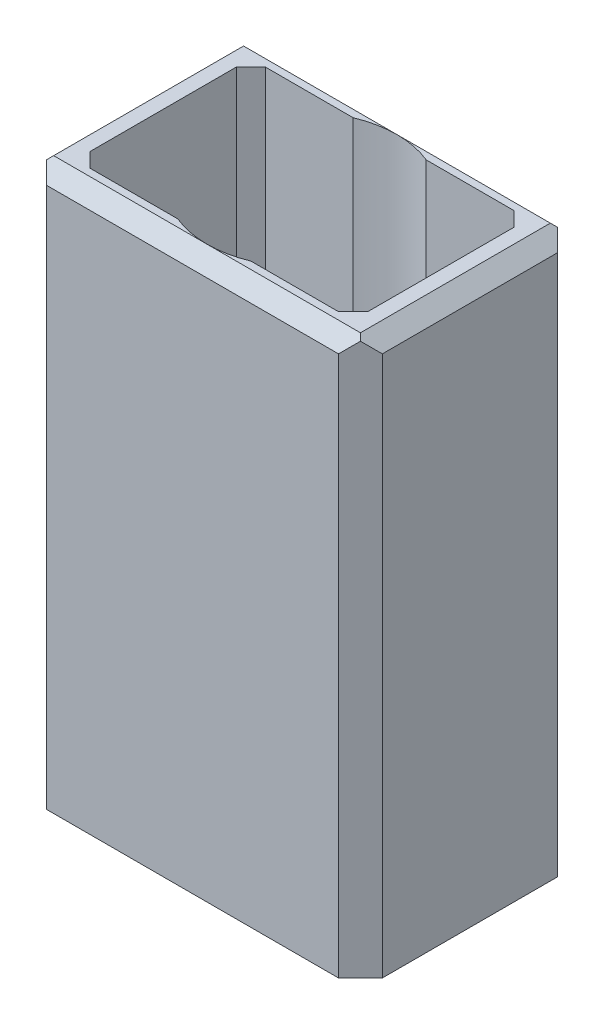
SolidWorks part; units mm, degrees
ref_plane "Front Plane" through (0, 0, 0) normal (0, 0, 1) x (1, 0, 0)
ref_plane "Top Plane" through (0, 0, 0) normal (0, 1, 0) x (1, 0, 0)
ref_plane "Right Plane" through (0, 0, 0) normal (1, 0, 0) x (0, 0, -1)
sketch "Sketch1" plane through (0, 0, 0) normal (0, 1, 0) x (1, 0, 0)
  line L1 (-9.5, -6) -> (9.5, -6)
  line L2 (-9.5, -6) -> (-9.5, 6)
  line L3 (-9.5, 6) -> (9.5, 6)
  line L4 (9.5, -6) -> (9.5, 6)
  line L5 (-9.5, -6) -> (9.5, 6) construction
  line L6 (-9.5, 6) -> (9.5, -6) construction
  line L7 (-11.5, -7.5) -> (11.5, -7.5)
  line L8 (-11.5, -7.5) -> (-11.5, 7.5)
  line L9 (-11.5, 7.5) -> (11.5, 7.5)
  line L10 (11.5, -7.5) -> (11.5, 7.5)
  line L11 (-11.5, -7.5) -> (11.5, 7.5) construction
  line L12 (-11.5, 7.5) -> (11.5, -7.5) construction
  point P0 (0, 0)
  point P6 (0, 0)
  dimension "D1" = 19
  dimension "D2" = 12
  dimension "D3" = 1.5
  dimension "D4" = 2
extrude "Boss-Extrude1" add sketch "Sketch1" along normal blind 35
chamfer "Chamfer1" distance 1 angle 45 4 edges at (-11.5, 35, 0) (0, 35, -7.5) (11.5, 35, 0) (0, 35, 7.5)
chamfer "Chamfer2" distance 1 angle 45 4 edges at (-9.5, 17.5, 6) (9.5, 17.5, 6) (-9.5, 17.5, -6) (9.5, 17.5, -6)
sketch "Sketch2" plane through (0, 0, 0) normal (0, -1, 0) x (1, 0, 0)
  line L1 (11.5, -7.5) -> (-11.5, -7.5)
  line L2 (11.5, -7.5) -> (11.5, 7.5)
  line L3 (11.5, 7.5) -> (-11.5, 7.5)
  line L4 (-11.5, -7.5) -> (-11.5, 7.5)
  line L5 (11.5, -7.5) -> (-11.5, 7.5) construction
  line L6 (11.5, 7.5) -> (-11.5, -7.5) construction
  point P0 (0, 0)
extrude "Boss-Extrude2" add sketch "Sketch2" along normal blind 3
chamfer "Chamfer4" distance 1.5 angle 45 4 edges at (11.5, 15.5, 7.5) (11.5, 15.5, -7.5) (-11.5, 15.5, 7.5) (-11.5, 15.5, -7.5)
sketch "Sketch3" plane through (0, -3, 0) normal (0, -1, 0) x (1, 0, 0)
  circle A0 centre (0, 0) radius 2.5
  dimension "D1" = 5
extrude "Cut-Extrude1" cut sketch "Sketch3" against normal blind 3
sketch "Sketch5" plane through (0, 0, 0) normal (0, 1, 0) x (1, 0, 0)
  circle A0 centre (0, 0) radius 6.5
  dimension "D1" = 13
extrude "Cut-Extrude3" cut sketch "Sketch5" along normal blind 40
